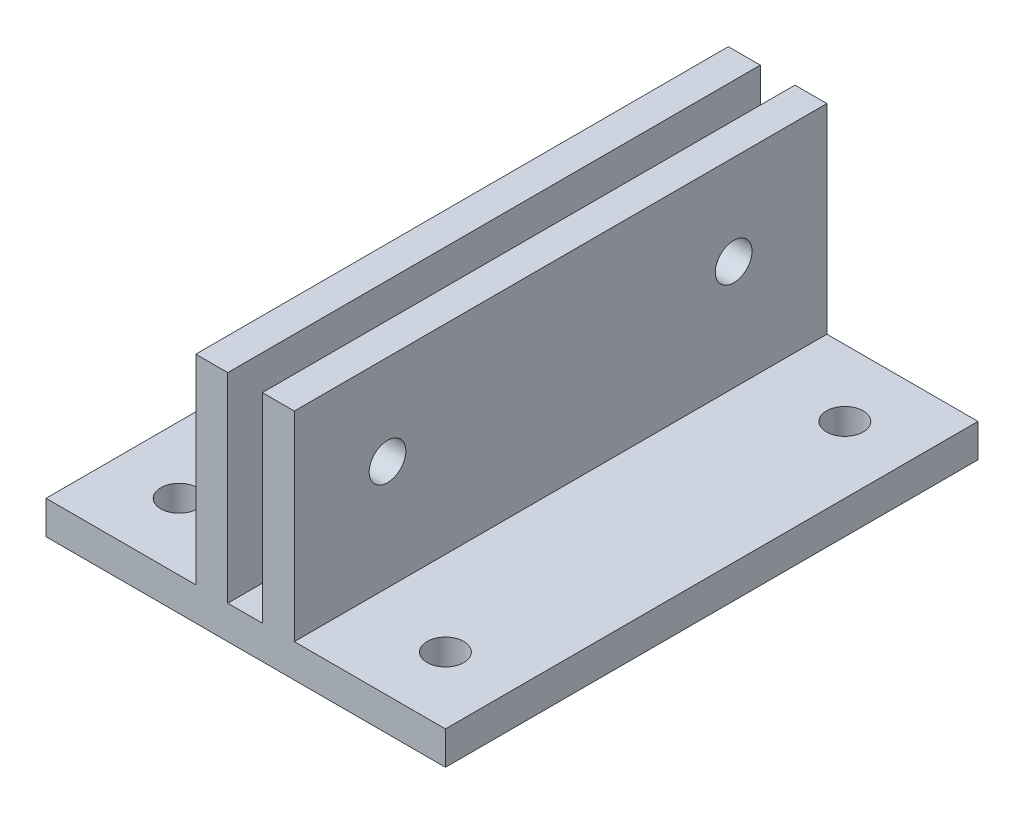
SolidWorks part; units mm, degrees
ref_plane "Front Plane" through (0, 0, 0) normal (0, 0, 1) x (1, 0, 0)
ref_plane "Top Plane" through (0, 0, 0) normal (0, 1, 0) x (1, 0, 0)
ref_plane "Right Plane" through (0, 0, 0) normal (1, 0, 0) x (0, 0, -1)
sketch "Sketch1" plane through (0, 0, 0) normal (0, 1, 0) x (1, 0, 0)
  line L1 (-19.05, -25.4) -> (19.05, -25.4)
  line L2 (-19.05, -25.4) -> (-19.05, 25.4)
  line L3 (-19.05, 25.4) -> (19.05, 25.4)
  line L4 (19.05, -25.4) -> (19.05, 25.4)
  line L5 (-19.05, -25.4) -> (19.05, 25.4) construction
  line L6 (-19.05, 25.4) -> (19.05, -25.4) construction
  point P0 (0, 0)
  dimension "D1" = 50.8
  dimension "D2" = 38.1
extrude "Boss-Extrude1" add sketch "Sketch1" along normal blind 3.175
sketch "Sketch2" plane through (0, 3.175, 0) normal (0, 1, 0) x (1, 0, 0)
  line L0 (-19.05, -25.4) -> (19.05, -25.4) construction
  line L1 (-4.7625, -25.4) -> (-1.7145, -25.4)
  line L2 (-4.7625, -25.4) -> (-4.7625, 25.4)
  line L3 (-4.7625, 25.4) -> (-1.7145, 25.4)
  line L4 (-1.7145, -25.4) -> (-1.7145, 25.4)
  line L5 (19.05, 25.4) -> (-19.05, 25.4) construction
  line L7 (1.5875, -25.4) -> (4.6355, -25.4)
  line L8 (1.5875, -25.4) -> (1.5875, 25.4)
  line L9 (1.5875, 25.4) -> (4.6355, 25.4)
  line L10 (4.6355, -25.4) -> (4.6355, 25.4)
  point P12 (0, 25.4)
  point P14 (6.4901, 25.4)
  dimension "D1" = 3.048
  dimension "D2" = 3.302
  dimension "D3" = 1.5875
extrude "Boss-Extrude2" add sketch "Sketch2" along normal blind 19.05
sketch "Sketch3" plane through (0, 3.175, 0) normal (0, 1, 0) x (1, 0, 0)
  line L0 (-19.05, 25.4) -> (-19.05, -25.4) construction
  line L3 (-4.7625, 25.4) -> (-19.05, 25.4) construction
  line L4 (-19.05, -25.4) -> (-4.7625, -25.4) construction
  line L5 (19.05, -25.4) -> (19.05, 25.4) construction
  circle A0 centre (-12.7, 19.05) radius 1.75
  circle A1 centre (-12.7, -19.05) radius 1.75
  circle A2 centre (12.7, -19.05) radius 1.75
  circle A3 centre (12.7, 19.05) radius 1.75
  point P12 (-15.3926, 25.4)
  dimension "D3" = 3.5
  dimension "D1" = 6.35
  dimension "D2" = 6.35
  dimension "D4" = 6.35
  dimension "D5" = 6.35
extrude "Cut-Extrude1" cut sketch "Sketch3" against normal through all
sketch "Sketch4" plane through (-4.7625, 0, 0) normal (-1, 0, 0) x (0, 0, 1)
  line L0 (-25.4, 22.225) -> (-25.4, 3.175) construction
  line L1 (25.4, 22.225) -> (25.4, 3.175) construction
  circle A0 centre (-16.51, 13.6128) radius 1.75
  circle A1 centre (16.51, 13.6128) radius 1.75
  dimension "D1" = 3.5
  dimension "D2" = 3.5
  dimension "D3" = 8.89
  dimension "D4" = 8.89
extrude "Cut-Extrude2" cut sketch "Sketch4" against normal through all
